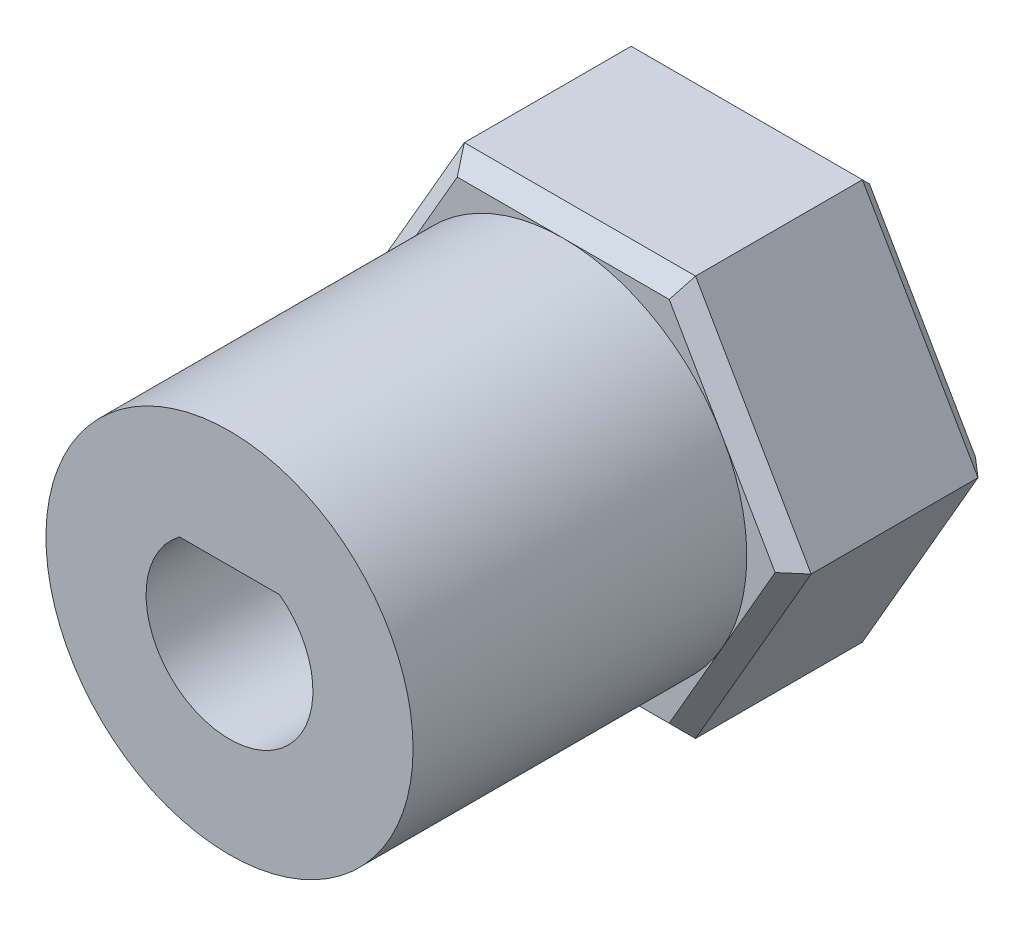
SolidWorks part; units mm, degrees
ref_plane "前视基准面" through (0, 0, 0) normal (0, 0, 1) x (1, 0, 0)
ref_plane "上视基准面" through (0, 0, 0) normal (0, 1, 0) x (1, 0, 0)
ref_plane "右视基准面" through (0, 0, 0) normal (1, 0, 0) x (0, 0, -1)
other "Configuration Table"
sketch "草图1" plane through (0, 0, 0) normal (0, 0, 1) x (1, 0, 0)
  line L1 (3.4641, 6) -> (-3.4641, 6)
  line L2 (-3.4641, 6) -> (-6.9282, 0)
  line L3 (-6.9282, 0) -> (-3.4641, -6)
  line L4 (-3.4641, -6) -> (3.4641, -6)
  line L5 (3.4641, -6) -> (6.9282, 0)
  line L6 (6.9282, 0) -> (3.4641, 6)
  circle A0 centre (0, 0) radius 6 construction
  circle A1 centre (0, 0) radius 1.75
  dimension "D2" = 3.5
  dimension "D1" = 12
extrude "凸台-拉伸1" add sketch "草图1" along normal blind 6
chamfer "倒角1" distance 0.5 12 edges at (0, 6, 0) (-5.1962, 3, 0) (-5.1962, -3, 0) (0, -6, 0) (5.1962, -3, 0) (5.1962, 3, 0) (-5.1962, -3, 6) (0, -6, 6) (5.1962, -3, 6) (5.1962, 3, 6) (0, 6, 6) (-5.1962, 3, 6)
sketch "草图2" plane through (0, 0, 6) normal (0, 0, 1) x (1, 0, 0)
  line L0 (-1.5, 2) -> (1.5, 2)
  circle A0 centre (0, 0) radius 5.5
  arc A1 (-1.5, 2) -> (1.5, 2) centre (0, 0) ccw
  dimension "D1" = 11
  dimension "D2" = 5
  dimension "D3" = 2
extrude "凸台-拉伸2" add sketch "草图2" along normal blind 10
